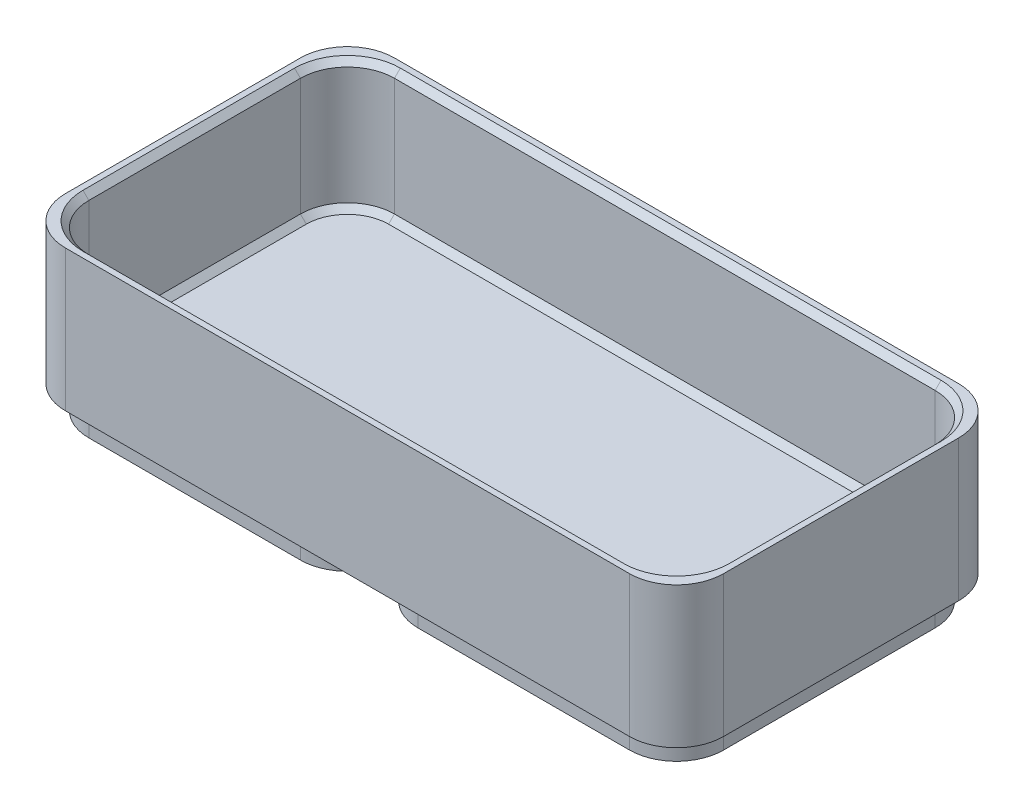
SolidWorks part; units mm, degrees
ref_plane "Front Plane" through (0, 0, 0) normal (0, 0, 1) x (1, 0, 0)
ref_plane "Top Plane" through (0, 0, 0) normal (0, 1, 0) x (1, 0, 0)
ref_plane "Right Plane" through (0, 0, 0) normal (1, 0, 0) x (0, 0, -1)
sketch "Sketch5" plane through (0, 0, 0) normal (0, 1, 0) x (1, 0, 0)
  line L1 (-22.5, -32.5) -> (22.5, -32.5)
  line L2 (-32.5, -22.5) -> (-32.5, 22.5)
  line L3 (-22.5, 32.5) -> (22.5, 32.5)
  line L4 (32.5, -22.5) -> (32.5, 22.5)
  line L5 (-32.5, -32.5) -> (32.5, 32.5) construction
  line L6 (-32.5, 32.5) -> (32.5, -32.5) construction
  arc A0 (-22.5, -32.5) -> (-32.5, -22.5) centre (-22.5, -22.5) cw
  arc A1 (22.5, -32.5) -> (32.5, -22.5) centre (22.5, -22.5) ccw
  arc A2 (22.5, 32.5) -> (32.5, 22.5) centre (22.5, 22.5) cw
  arc A3 (-32.5, 22.5) -> (-22.5, 32.5) centre (-22.5, 22.5) cw
  point P0 (0, 0)
  dimension "D3" = 10
  dimension "D1" = 65
  dimension "D2" = 65
extrude "Boss-Extrude4" add sketch "Sketch5" along normal blind 5
sketch "Sketch6" plane through (0, 5, 0) normal (0, 1, 0) x (1, 0, 0)
  line L1 (35, 35) -> (-35, 35)
  line L2 (35, 35) -> (35, -35)
  line L3 (35, -35) -> (-35, -35)
  line L4 (-35, 35) -> (-35, -35)
  line L5 (35, 35) -> (-35, -35) construction
  line L6 (35, -35) -> (-35, 35) construction
  point P0 (0, 0)
extrude "Boss-Extrude5" add sketch "Sketch6" along normal blind 30
sketch "Sketch8" plane through (0, 0, 0) normal (0, -1, 0) x (1, 0, 0)
  line L0 (-29.5711, 29.5711) -> (-22.5, 22.5)
  arc A0 (-22.5, 32.5) -> (-32.5, 22.5) centre (-22.5, 22.5) ccw construction
  circle A1 centre (-26.0355, 26.0355) radius 3
  circle A2 centre (26.0365, 26.0365) radius 3
  circle A3 centre (26.0375, -26.0355) radius 3
  circle A4 centre (-26.0345, -26.0365) radius 3
  point P8 (0, 0)
  point P15 (0.001, 0.001)
  point P18 (0.002, 0)
  point P21 (0.001, -0.001)
  point P22 (0.001, 0)
  dimension "D1" = 4
extrude "Cut-Extrude1" cut sketch "Sketch8" against normal blind 2 contours A3 | A2 | L0 A1 | L0 A1 | A4
mirror "Mirror1" about plane through (-35, 35, -35) normal (1, 0, 0) of bodies 112
sketch "Sketch9" plane through (0, 35, 0) normal (0, 1, 0) x (1, 0, 0)
  line L8 (32.5, 32.5) -> (-102.5, 32.5)
  line L9 (-102.5, 32.5) -> (-102.5, -32.5)
  line L10 (-102.5, -32.5) -> (32.5, -32.5)
  line L11 (32.5, -32.5) -> (32.5, 32.5)
  line L12 (22.5, 32.5) -> (-92.5, 32.5)
  line L13 (-102.5, 22.5) -> (-102.5, -22.5)
  line L14 (-92.5, -32.5) -> (22.5, -32.5)
  line L15 (32.5, -22.5) -> (32.5, 22.5)
  arc A0 (-102.5, -22.5) -> (-92.5, -32.5) centre (-92.5, -22.5) ccw
  arc A1 (22.5, -32.5) -> (32.5, -22.5) centre (22.5, -22.5) ccw
  arc A2 (22.5, 32.5) -> (32.5, 22.5) centre (22.5, 22.5) cw
  arc A3 (-92.5, 32.5) -> (-102.5, 22.5) centre (-92.5, 22.5) ccw
  dimension "D2" = 10
  dimension "D1" = 2.5
extrude "Cut-Extrude2" cut sketch "Sketch9" against normal blind 30
sketch "Sketch10" plane through (0, 5, 0) normal (0, -1, 0) x (1, 0, 0)
  line L8 (35, 35) -> (-105, 35)
  line L9 (-105, 35) -> (-105, -35)
  line L10 (-105, -35) -> (35, -35)
  line L11 (35, -35) -> (35, 35)
  line L12 (35, 35) -> (-105, 35)
  line L13 (-105, 35) -> (-105, -35)
  line L14 (-105, -35) -> (35, -35)
  line L15 (35, -35) -> (35, 35)
  dimension "D1" = 0
extrude "Boss-Extrude6" add sketch "Sketch10" against normal blind 2.5
fillet "Fillet1" radius 10 4 edges at (35, 20, -35) (35, 20, 35) (-105, 20, 35) (-105, 20, -35)
chamfer "Chamfer1" distance 1.25 angle 45 8 edges at (-35, 7.5, 32.5) (29.5711, 7.5, 29.5711) (-99.5711, 7.5, 29.5711) (32.5, 7.5, 0) (-102.5, 7.5, 0) (29.5711, 7.5, -29.5711) (-99.5711, 7.5, -29.5711) (-35, 7.5, -32.5)
chamfer "Chamfer2" distance 1.25 angle 45 8 edges at (-99.5711, 35, 29.5711) (-35, 35, 32.5) (-102.5, 35, 0) (29.5711, 35, 29.5711) (-99.5711, 35, -29.5711) (32.5, 35, 0) (-35, 35, -32.5) (29.5711, 35, -29.5711)
